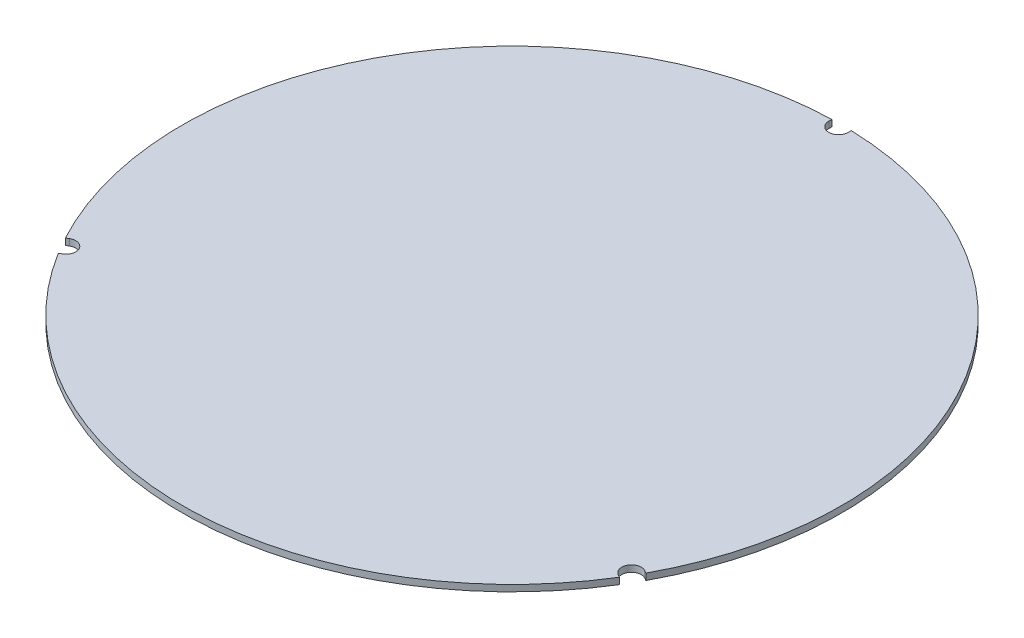
SolidWorks part; units mm, degrees
ref_plane "前视基准面" through (0, 0, 0) normal (0, 0, 1) x (1, 0, 0)
ref_plane "上视基准面" through (0, 0, 0) normal (0, 1, 0) x (1, 0, 0)
ref_plane "右视基准面" through (0, 0, 0) normal (1, 0, 0) x (0, 0, -1)
other "Configuration Table"
sketch "草图1" plane through (0, 0, 0) normal (0, 1, 0) x (1, 0, 0)
  circle A0 centre (0, 0) radius 51
  dimension "D1" = 102
extrude "凸台-拉伸1" add sketch "草图1" along normal blind 1
sketch "草图2" plane through (0, 1, 0) normal (0, 1, 0) x (1, 0, 0)
  line L0 (0, 0) -> (0, 50.5) construction
  line L1 (0, 0) -> (-43.7343, -25.25) construction
  line L2 (0, 0) -> (43.7343, -25.25) construction
  circle A0 centre (0, 0) radius 50.5 construction
  circle A1 centre (0, 50.5) radius 1.5
  circle A4 centre (-43.7343, -25.25) radius 1.5
  circle A5 centre (43.7343, -25.25) radius 1.5
  dimension "D1" = 101
  dimension "D4" = 3
  dimension "D5" = 3
  dimension "D6" = 3
  dimension "D2" = 120
  dimension "D3" = 120
extrude "切除-拉伸1" cut sketch "草图2" against normal through all
sketch "草图3" plane through (0, 1, 0) normal (0, 1, 0) x (1, 0, 0)
  line L0 (-44.4843, -23.951) -> (-45.3503, -24.451)
  line L1 (-1.5, 51.5) -> (1.5, 51.5)
  line L2 (-1.5, 51.5) -> (-1.5, 50.5)
  line L3 (-1.5, 50.5) -> (1.5, 50.5)
  line L4 (1.5, 51.5) -> (1.5, 50.5)
  line L5 (-1.5, 51.5) -> (1.5, 50.5) construction
  line L6 (-1.5, 50.5) -> (1.5, 51.5) construction
  line L7 (-45.3503, -24.451) -> (-43.8503, -27.049)
  line L8 (-43.8503, -27.049) -> (-42.9843, -26.549)
  line L9 (-42.9843, -26.549) -> (-44.4843, -23.951)
  line L10 (44.4843, -23.951) -> (42.9843, -26.549)
  line L11 (42.9843, -26.549) -> (43.8503, -27.049)
  line L12 (43.8503, -27.049) -> (45.3503, -24.451)
  line L13 (45.3503, -24.451) -> (44.4843, -23.951)
  arc A0 (-1.4211, 50.9802) -> (1.4211, 50.9802) centre (0, 50.5) ccw construction
  arc A1 (-1.4211, 50.9802) -> (1.4211, 50.9802) centre (0, 50.5) ccw construction
  arc A2 (44.8607, -24.2594) -> (43.4396, -26.7208) centre (43.7343, -25.25) ccw construction
  arc A3 (44.8607, -24.2594) -> (43.4396, -26.7208) centre (43.7343, -25.25) ccw construction
  arc A4 (-43.4396, -26.7208) -> (-44.8607, -24.2594) centre (-43.7343, -25.25) ccw construction
  arc A5 (-43.4396, -26.7208) -> (-44.8607, -24.2594) centre (-43.7343, -25.25) ccw construction
  point P3 (0, 51)
  point P19 (43.7343, -25.25)
  point P24 (-43.7343, -25.25)
  dimension "D1" = 3
  dimension "D2" = 1
  dimension "D3" = 30
  dimension "D4" = 3
  dimension "D5" = 1
  dimension "D6" = 30
  dimension "D7" = 3
  dimension "D8" = 1
extrude "切除-拉伸2" cut sketch "草图3" against normal through all
